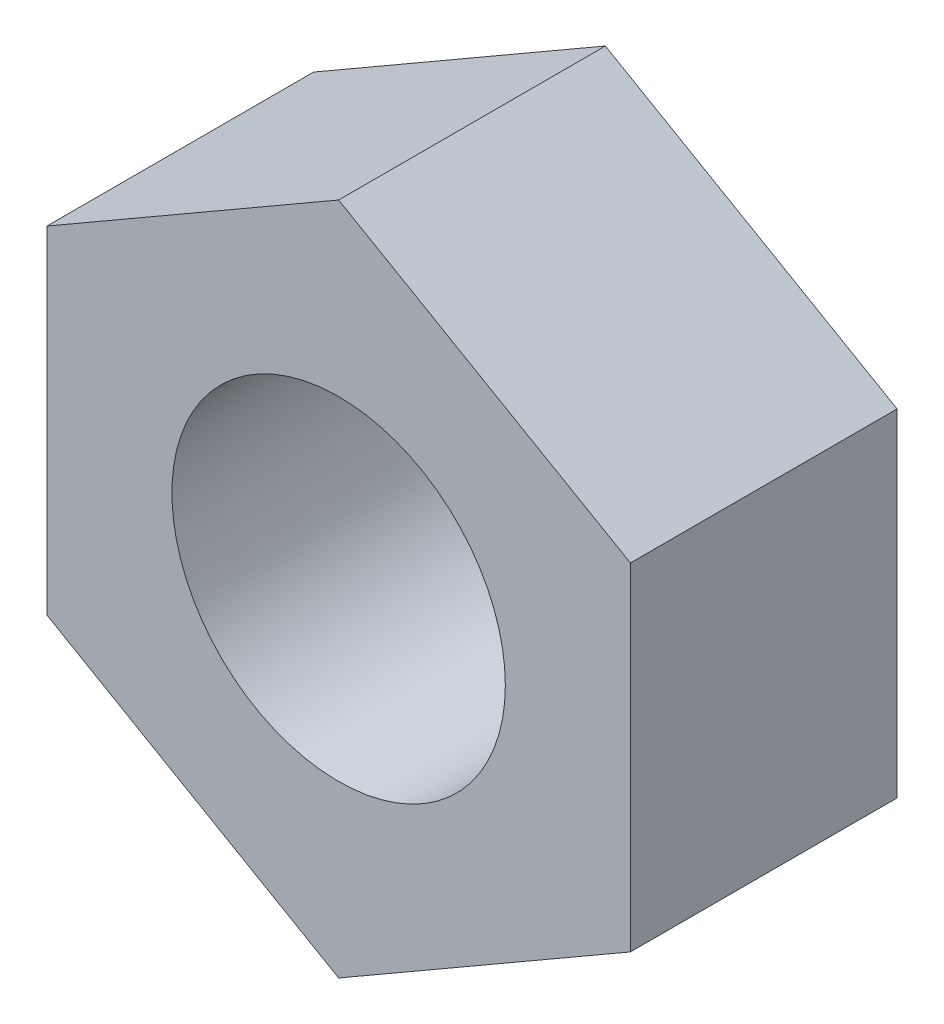
SolidWorks part; units mm, degrees
ref_plane "Front Plane" through (0, 0, 0) normal (1, 0, 0) x (0, 1, 0)
ref_plane "Top Plane" through (0, 0, 0) normal (0, 0, 1) x (0, 1, 0)
ref_plane "Right Plane" through (0, 0, 0) normal (0, 1, 0) x (-1, 0, 0)
sketch "Sketch1" plane through (0, 0, 0) normal (0, 0, 1) x (0, 1, 0)
  line L1 (3.0311, 0) -> (1.5155, 2.625)
  line L2 (1.5155, 2.625) -> (-1.5155, 2.625)
  line L3 (-1.5155, 2.625) -> (-3.0311, 0)
  line L4 (-3.0311, 0) -> (-1.5155, -2.625)
  line L5 (-1.5155, -2.625) -> (1.5155, -2.625)
  line L6 (1.5155, -2.625) -> (3.0311, 0)
  circle A0 centre (0, 0) radius 2.625 construction
  circle A1 centre (0, 0) radius 1.5
  dimension "D1" = 3
  dimension "D2" = 5.25
extrude "Boss-Extrude1" add sketch "Sketch1" along normal blind 2.4
